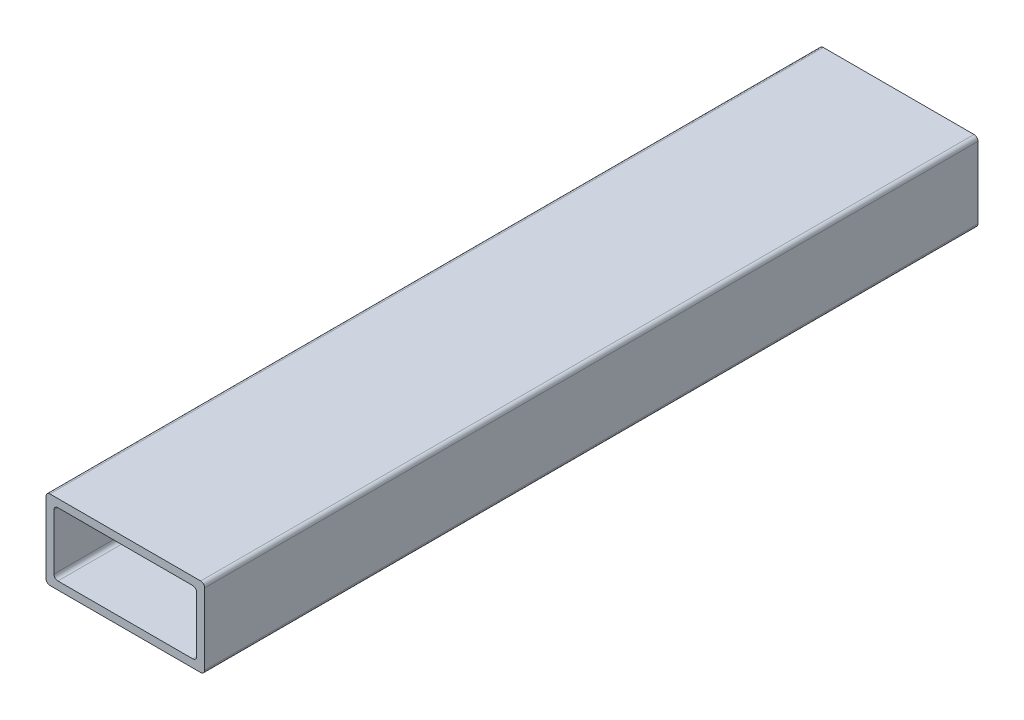
SolidWorks part; units mm, degrees
ref_plane "Plan de face" through (0, 0, 0) normal (0, 0, 1) x (1, 0, 0)
ref_plane "Plan de dessus" through (0, 0, 0) normal (0, 1, 0) x (1, 0, 0)
ref_plane "Plan de droite" through (0, 0, 0) normal (1, 0, 0) x (0, 0, -1)
sketch "Esquisse2" plane through (0, 0, 0) normal (0, 0, 1) x (1, 0, 0)
  line L0 (6, 4) -> (74, 4)
  line L1 (2, 0) -> (78, 0)
  line L2 (0, 2) -> (0, 38)
  line L3 (2, 40) -> (78, 40)
  line L4 (80, 2) -> (80, 38)
  line L5 (76, 6) -> (76, 34)
  line L6 (6, 36) -> (74, 36)
  line L7 (4, 6) -> (4, 34)
  line L8 (4, 4) -> (76, 4) construction
  line L9 (76, 4) -> (76, 36) construction
  line L10 (4, 36) -> (76, 36) construction
  line L11 (4, 4) -> (4, 36) construction
  line L12 (0, 0) -> (80, 0) construction
  line L13 (0, 0) -> (0, 40) construction
  line L14 (0, 40) -> (80, 40) construction
  line L15 (80, 0) -> (80, 40) construction
  arc A0 (74, 4) -> (76, 6) centre (74, 6) ccw
  arc A1 (76, 34) -> (74, 36) centre (74, 34) ccw
  arc A2 (6, 36) -> (4, 34) centre (6, 34) ccw
  arc A3 (4, 6) -> (6, 4) centre (6, 6) ccw
  arc A4 (2, 0) -> (0, 2) centre (2, 2) cw
  arc A5 (0, 38) -> (2, 40) centre (2, 38) cw
  arc A6 (78, 40) -> (80, 38) centre (78, 38) cw
  arc A7 (80, 2) -> (78, 0) centre (78, 2) cw
  point P24 (0, 0)
  dimension "D4" = 2
  dimension "D1" = 40
  dimension "D2" = 80
  dimension "D3" = 4
extrude "Boss.-Extru.1" add sketch "Esquisse2" along normal blind 390
